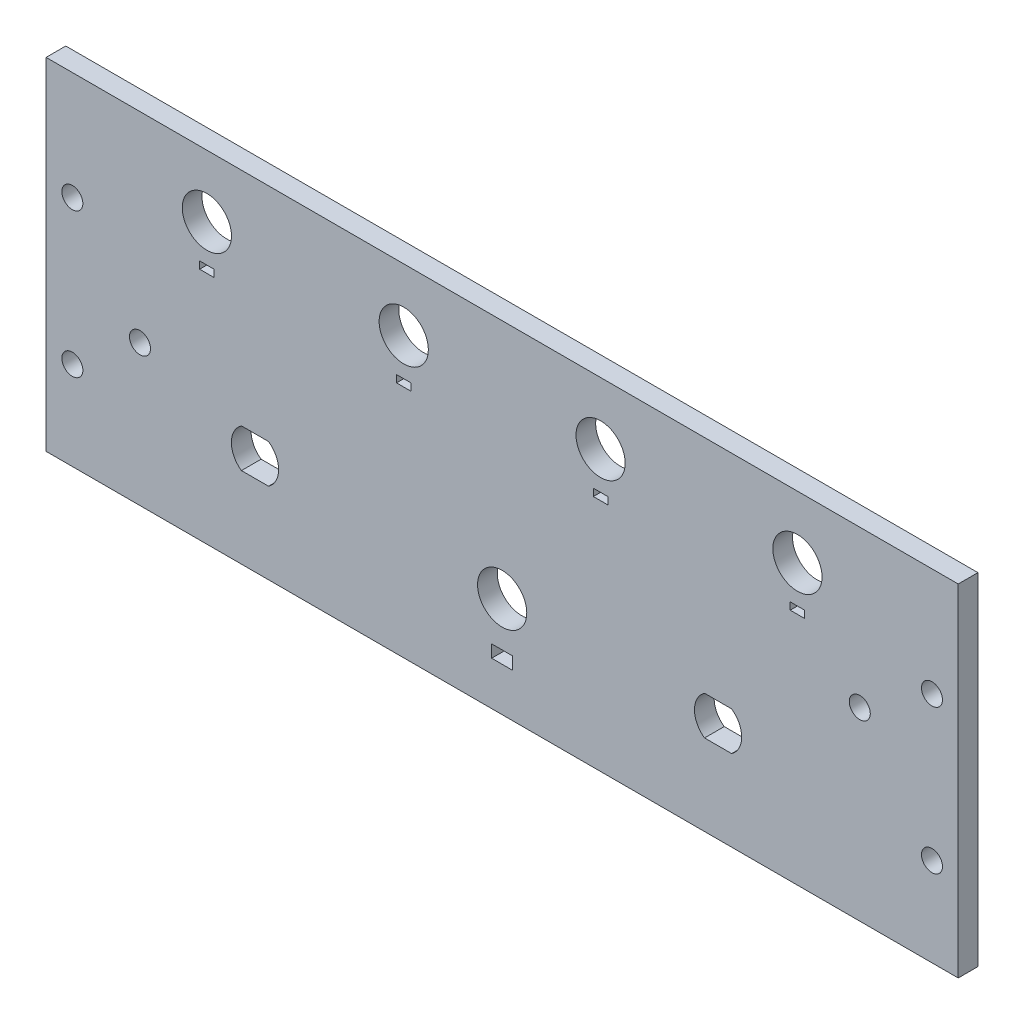
SolidWorks part; units mm, degrees
ref_plane "Front Plane" through (0, 0, 0) normal (0, 0, 1) x (1, 0, 0)
ref_plane "Top Plane" through (0, 0, 0) normal (0, 1, 0) x (1, 0, 0)
ref_plane "Right Plane" through (0, 0, 0) normal (1, 0, 0) x (0, 0, -1)
sketch "Sketch1" plane through (0, 0, 0) normal (0, 0, 1) x (1, 0, 0)
  line L0 (67.9, 6.6516) -> (71.1, 6.6516)
  line L1 (0, 0) -> (139, 0)
  line L2 (0, 0) -> (0, 52)
  line L3 (0, 52) -> (139, 52)
  line L4 (139, 0) -> (139, 52)
  line L5 (69.5, 52) -> (69.5, 0) construction
  line L17 (24.5, 42.5415) -> (24.5, 36.2915) construction
  line L30 (23.4, 35.7415) -> (25.6, 35.7415)
  line L31 (23.4, 35.7415) -> (23.4, 36.8415)
  line L45 (100.3397, 12.3516) -> (104.4664, 12.3516)
  line L52 (104.4664, 18.2516) -> (100.3397, 18.2516)
  line L53 (23.4, 36.8415) -> (25.6, 36.8415)
  line L66 (25.6, 35.7415) -> (25.6, 36.8415)
  line L67 (23.4, 35.7415) -> (25.6, 36.8415) construction
  line L68 (23.4, 36.8415) -> (25.6, 35.7415) construction
  line L69 (67.9, 6.6516) -> (67.9, 8.5516)
  line L70 (67.9, 8.5516) -> (71.1, 8.5516)
  line L71 (71.1, 6.6516) -> (71.1, 8.5516)
  line L72 (67.9, 6.6516) -> (71.1, 8.5516) construction
  line L73 (67.9, 8.5516) -> (71.1, 6.6516) construction
  line L74 (29.7679, 12.3516) -> (33.8946, 12.3516)
  line L75 (33.8946, 18.2516) -> (29.7679, 18.2516)
  line L76 (53.4, 35.7415) -> (55.6, 35.7415)
  line L77 (53.4, 35.7415) -> (53.4, 36.8415)
  line L78 (53.4, 36.8415) -> (55.6, 36.8415)
  line L79 (55.6, 35.7415) -> (55.6, 36.8415)
  line L80 (54.5, 42.5415) -> (54.5, 36.2915) construction
  line L81 (53.4, 35.7415) -> (55.6, 36.8415) construction
  line L82 (53.4, 36.8415) -> (55.6, 35.7415) construction
  line L83 (83.4, 35.7415) -> (85.6, 35.7415)
  line L84 (83.4, 35.7415) -> (83.4, 36.8415)
  line L85 (83.4, 36.8415) -> (85.6, 36.8415)
  line L86 (85.6, 35.7415) -> (85.6, 36.8415)
  line L87 (84.5, 42.5415) -> (84.5, 36.2915) construction
  line L88 (83.4, 35.7415) -> (85.6, 36.8415) construction
  line L89 (83.4, 36.8415) -> (85.6, 35.7415) construction
  line L90 (113.4, 35.7415) -> (115.6, 35.7415)
  line L91 (113.4, 35.7415) -> (113.4, 36.8415)
  line L92 (113.4, 36.8415) -> (115.6, 36.8415)
  line L93 (115.6, 35.7415) -> (115.6, 36.8415)
  line L94 (114.5, 42.5415) -> (114.5, 36.2915) construction
  line L95 (113.4, 35.7415) -> (115.6, 36.8415) construction
  line L96 (113.4, 36.8415) -> (115.6, 35.7415) construction
  circle A4 centre (4, 35.5) radius 1.6
  circle A5 centre (135, 35.5) radius 1.6
  circle A6 centre (135, 13.5) radius 1.6
  circle A7 centre (4, 13.5) radius 1.6
  circle A9 centre (14.3091, 21.5) radius 1.6
  circle A11 centre (124, 28.1942) radius 1.6
  circle A17 centre (69.5, 15.3016) radius 3.75
  arc A19 (29.7679, 18.2516) -> (29.7679, 12.3516) centre (31.8312, 15.3016) ccw
  arc A20 (33.8946, 12.3516) -> (33.8946, 18.2516) centre (31.8312, 15.3016) ccw
  circle A21 centre (31.8312, 15.3016) radius 3.6 construction
  arc A22 (100.3397, 18.2516) -> (100.3397, 12.3516) centre (102.403, 15.3016) ccw
  arc A23 (104.4664, 12.3516) -> (104.4664, 18.2516) centre (102.403, 15.3016) ccw
  circle A24 centre (102.403, 15.3016) radius 3.6 construction
  circle A27 centre (24.5, 42.5415) radius 3.75
  circle A28 centre (54.5, 42.5415) radius 3.75
  circle A29 centre (84.5, 42.5415) radius 3.75
  circle A30 centre (114.5, 42.5415) radius 3.75
  point P5 (24.7401, 42.5415)
  point P8 (0, 26)
  point P14 (69.5, 7.6016)
  point P39 (24.5, 36.2915)
  point P47 (0, 0)
  point P48 (54.5, 36.2915)
  point P56 (84.5, 36.2915)
  point P64 (114.5, 36.2915)
  point P70 (124, 28.1942)
  point P71 (84.6709, 43.3344)
  dimension "D4" = 7.5
  dimension "D5" = 3.2
  dimension "D8" = 3.2
  dimension "D24" = 7.7
  dimension "D25" = 21.5
  dimension "D29" = 7.2
  dimension "D19" = 3.2
  dimension "D6" = 1.9
  dimension "D16" = 7.2
  dimension "D21" = 2.2
  dimension "D23" = 7.5
  dimension "D1" = 139
  dimension "D2" = 52
  dimension "D7" = 5.9
  dimension "D11" = 131
  dimension "D12" = 4
  dimension "D13" = 13.5
  dimension "D14" = 22
  dimension "D17" = 15
  dimension "D18" = 15
  dimension "D20" = 4
  dimension "D22" = 1.1
  dimension "D26" = 5.7
  dimension "D27" = 24.5
  dimension "D28" = 30
  dimension "D35" = 5.9
  dimension "D9" = 2
  dimension "D10" = 2
extrude "Boss-Extrude1" add sketch "Sketch1" along normal blind 3
